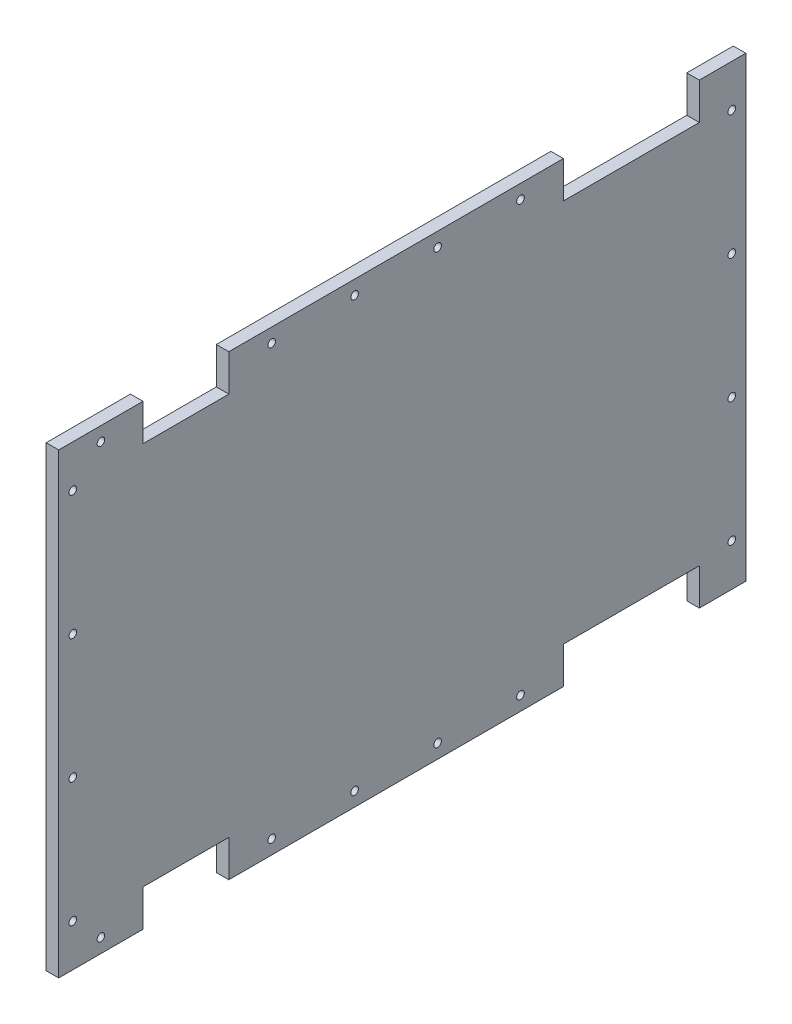
SolidWorks part; units mm, degrees
material "Cedar"
ref_plane "Front Plane" through (0, 0, 0) normal (0, 0, 1) x (1, 0, 0)
ref_plane "Top Plane" through (0, 0, 0) normal (0, 1, 0) x (1, 0, 0)
ref_plane "Right Plane" through (0, 0, 0) normal (1, 0, 0) x (0, 0, -1)
sketch "Sketch1" plane through (0, 0, 0) normal (1, 0, 0) x (0, 0, -1)
  line L0 (305, -203) -> (-305, -203) construction
  line L1 (-305, -203) -> (305, -203)
  line L2 (-305, -203) -> (-305, 203)
  line L3 (-305, 203) -> (305, 203)
  line L4 (305, -203) -> (305, 203)
  line L5 (-305, -203) -> (305, 203) construction
  line L6 (-305, 203) -> (305, -203) construction
  line L7 (305, -203) -> (-305, -203)
  line L8 (305, 203) -> (-305, 203) construction
  line L9 (305, 203) -> (-305, 203)
  line L10 (305, -203) -> (-305, -203)
  point P0 (0, 0)
extrude "Boss-Extrude1" add sketch "Sketch1" along normal blind 11.1125 contours L1 L4 L3 L2
sketch "Sketch3" plane through (11.1125, 0, 0) normal (1, 0, 0) x (0, 0, -1)
  line L1 (263.725, 203) -> (143.075, 203)
  line L2 (263.725, 203) -> (263.725, 170.38)
  line L3 (263.725, 170.38) -> (143.075, 170.38)
  line L4 (143.075, 203) -> (143.075, 170.38)
  line L6 (155.775, 171.65) -> (251.025, 171.65) construction
  line L7 (-305, 203) -> (305, 203) construction
  line L8 (251.025, 171.65) -> (251.025, 178) construction
  line L9 (155.775, 178) -> (155.775, 171.65) construction
  line L10 (251.025, 171.65) -> (251.025, 178)
  line L11 (155.775, 178) -> (155.775, 171.65)
  line L12 (160.855, 171.65) -> (245.945, 171.65) construction
  line L13 (203.4, 171.65) -> (203.4, 170.38) construction
  point P9 (203.4, 170.38)
  dimension "D1" = 1.27
  dimension "D2" = 12.7
extrude "Cut-Extrude2" cut sketch "Sketch3" against normal through all
sketch "Sketch8" plane through (11.1125, 0, 0) normal (1, 0, 0) x (0, 0, -1)
  line L0 (-192.0863, 170.38) -> (-192.0863, 203) construction
  line L1 (-230.1863, 203) -> (-153.9863, 203)
  line L2 (-230.1863, 203) -> (-230.1863, 170.38)
  line L3 (-230.1863, 170.38) -> (-153.9863, 170.38)
  line L4 (-153.9863, 203) -> (-153.9863, 170.38)
  line L5 (-305, 203) -> (143.075, 203) construction
  line L9 (-217.4863, 171.65) -> (-166.6863, 171.65) construction
  point P10 (-192.0863, 171.5967)
  point P11 (0, 0)
  dimension "D1" = 12.7
  dimension "D2" = 1.27
extrude "Cut-Extrude3" cut sketch "Sketch8" against normal through all
mirror "Mirror3" about plane through (0, 0, 0) normal (0, 1, 0) of "Cut-Extrude2", "Cut-Extrude3"
sketch "Sketch4" plane through (11.1125, 0, 0) normal (1, 0, 0) x (0, 0, -1)
  line L0 (0, 0) -> (305, 0) construction
  line L1 (-305, 203) -> (-280, 203) construction
  line L2 (-305, 203) -> (-305, -203) construction
  line L3 (-305, -203) -> (-280, -203) construction
  line L4 (-280, 203) -> (-280, -203) construction
  line L5 (-305, 203) -> (-230.1863, 203) construction
  line L6 (305, -203) -> (305, 203) construction
  line L7 (-292.5, -203) -> (-292.5, 203) construction
  line L9 (-153.9863, 203) -> (143.075, 203) construction
  line L10 (-305, -203) -> (-230.1863, -203) construction
  line L11 (0, 0) -> (0, 203) construction
  line L14 (-153.9863, 178) -> (143.075, 178) construction
  line L15 (-153.9863, 178) -> (-153.9863, 203) construction
  line L16 (-153.9863, 203) -> (143.075, 203) construction
  line L17 (143.075, 178) -> (143.075, 203) construction
  line L19 (-305, 190.5) -> (305, 190.5) construction
  line L22 (-153.9863, 170.38) -> (-153.9863, 203) construction
  line L23 (143.075, 203) -> (143.075, 170.38) construction
  line L24 (-305, -203) -> (-305, 203) construction
  circle A0 centre (-292.5, 165.5) radius 3.3782
  circle A1 centre (-292.5, 55.1667) radius 3.3782
  circle A2 centre (-292.5, -55.1667) radius 3.3782
  circle A3 centre (-292.5, -165.5) radius 3.3782
  circle A4 centre (292.5, -165.5) radius 3.3782
  circle A5 centre (292.5, -55.1667) radius 3.3782
  circle A6 centre (292.5, 165.5) radius 3.3782
  circle A7 centre (292.5, 55.1667) radius 3.3782
  circle A8 centre (-267.5, 190.5) radius 3.3782
  circle A9 centre (-115.8863, 190.5) radius 3.3782
  circle A11 centre (-42.2659, 190.5) radius 3.3782
  circle A12 centre (31.3546, 190.5) radius 3.3782
  circle A13 centre (104.975, 190.5) radius 3.3782
  circle A18 centre (104.975, -190.5) radius 3.3782
  circle A19 centre (31.3546, -190.5) radius 3.3782
  circle A20 centre (-42.2659, -190.5) radius 3.3782
  circle A21 centre (-115.8863, -190.5) radius 3.3782
  circle A22 centre (-267.5, -190.5) radius 3.3782
  point P53 (143.075, 190.5)
  dimension "D2" = 6.7564
  dimension "D1" = 25
  dimension "D3" = 37.5
  dimension "D5" = 37.5
  dimension "D6" = 37.5
  dimension "D7" = 38.1
  dimension "D9" = 38.1
  dimension "D4" = 4
  dimension "D8" = 4
extrude "Cut-Extrude4" cut sketch "Sketch4" against normal through all
equation "\"D3@Sketch4\"=\"D6@Sketch4\""
equation "\"D5@Sketch4\"=\"D3@Sketch4\""
